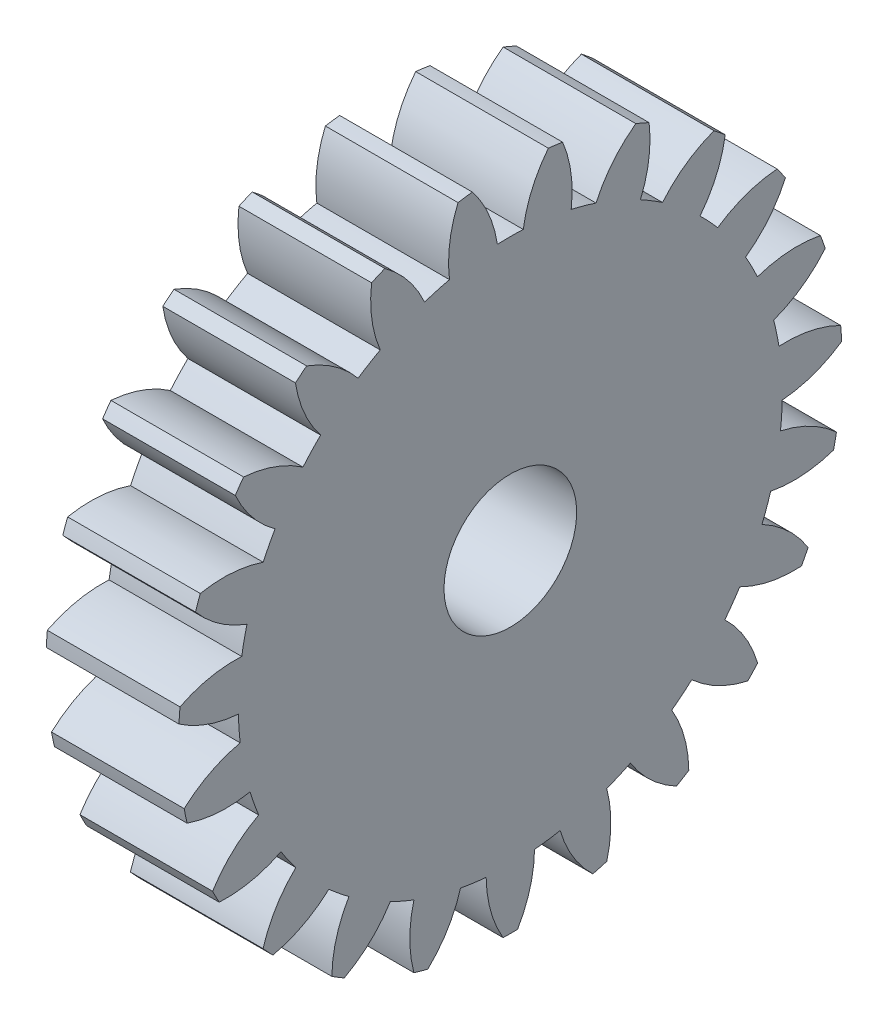
SolidWorks part; units mm, degrees
ref_plane "Plane1" through (0, 0, 0) normal (0, 0, 1) x (1, 0, 0)
ref_plane "Plane2" through (0, 0, 0) normal (0, 1, 0) x (1, 0, 0)
ref_plane "Plane3" through (0, 0, 0) normal (1, 0, 0) x (0, 0, -1)
other "Configuration Table"
sketch "HoldingSke" plane through (0, 0, 0) normal (0, 1, 0) x (1, 0, 0)
  line L0 (0, 0) -> (0.9205, -0.3907)
  line L1 (-15, 0) -> (100, 0) construction
  line L2 (0, 0) -> (-2.1039, 2.3779)
  line L3 (0, 0) -> (-11.863, 4.5341)
  line L4 (0, 0) -> (7.9495, 3.3744)
  line L5 (0, 0) -> (-46.8476, -17.4728)
  line L6 (0, 0) -> (-4.1448, -2.7965)
  line L7 (-2.1039, 2.3779) -> (8.6586, 51.2059)
  line L8 (-76.2, 54.61) -> (-75.3, 54.61)
  line L9 (-71.009, 38.7566) -> (-53.1078, 45.2721)
  line L10 (-76.2, 71.12) -> (104.1128, 71.12)
  line L11 (0, 0) -> (-5, 0)
  line L12 (-76.2, 101.6) -> (-76.162, 101.6)
  line L13 (24.9733, 27.94) -> (52.9518, 28.4284)
  line L14 (24.9733, 27.94) -> (24.9743, 27.94)
  line L15 (24.9733, 27.94) -> (100.4006, 29.5858)
  line L16 (-63.627, -1) -> (-12.827, -1)
  circle A0 centre (0, 0) radius 2.5
  circle A1 centre (0, 0) radius 10.249
  circle A2 centre (0, 0) radius 37.5
  circle A3 centre (0, 0) radius 2.5
  dimension "MHD" = 20.498
  dimension "Hub_dia" = 75
  dimension "Bore" = 5
  dimension "MBD" = 5
  dimension "Num_teeth" = 23
  dimension "Pitch" = 1
  dimension "Overall_len" = 50
  dimension "Show_teeth" = 23
  dimension "Thickness" = 5
  dimension "OAL" = 50.0001
  dimension "T_dim" = 0.9
  dimension "Ap" = 20
  dimension "H" = 19.05
  dimension "Pitch_radius" = 180.3128
  dimension "Width" = 5
  dimension "Backlash" = 0.038
  dimension "Addendum_fac" = 1
  dimension "Dedendum_fac" = 1.25
  dimension "Clearance_fac" = 0.25
  dimension "Dedendum_add" = 0.001
  dimension "Module" = 1
sketch "BasProSke" plane through (0, 0, 0) normal (0, 1, 0) x (1, 0, 0)
  line L0 (-10, 0) -> (60, 0) construction
  line L1 (0, 0) -> (0, 12.5)
  line L2 (0, 0) -> (5, 0)
  line L3 (5, 0) -> (5, 12.5)
  line L4 (5, 12.5) -> (0, 12.5)
  dimension "Thickness" = 5
  dimension "Diameter" = 25
revolve "Base-Revolve" add sketch "BasProSke" angle 360 about L0
sketch "TooCutSke" plane through (0, 0, 0) normal (1, 0, 0) x (0, 0, -1)
  line L1 (0, 0) -> (0, 107) construction
  line L2 (0, 0) -> (-0.8513, 11.4685) construction
  line L3 (0, 0) -> (-3.1257, 22.7413) construction
  line L4 (-0.8513, 11.4685) -> (-1.5629, 11.3706) construction
  arc A0 (0.4871, 10.2374) -> (-0.4871, 10.2374) centre (0, 0) ccw
  arc A1 (1.4505, 12.4411) -> (-1.4505, 12.4411) centre (0, 0) ccw
  circle A2 centre (0, 0) radius 11.5 construction
  circle A3 centre (0, 0) radius 10.8065 construction
  arc A4 (-0.4871, 10.2374) -> (-1.4505, 12.4411) centre (-5.037, 9.5608) ccw
  arc A5 (1.4505, 12.4411) -> (0.4871, 10.2374) centre (5.037, 9.5608) ccw
  dimension "Root_dia" = 20.498
  dimension "Overcut_dia" = 25.0508
  dimension "Pitch_dia" = 23
  dimension "Base_dia" = 21.6129
  dimension "Flank_rad" = 4.6
  dimension "Half_ang" = 7.826
  dimension "Half_CT" = 0.7183
extrude "ToothCut" cut sketch "TooCutSke" along normal through all
fillet "Breaks" [suppressed] radius 0.02
fillet "RootFillets" [suppressed] radius 0.251
pattern_circular "TeethCuts" count 23 every 15.652 about axis through (-10, 0, 0) along (1, 0, 0) of "ToothCut", "RootFillets", "Breaks"
sketch "HubNeaOneSke" plane through (0, 0, 0) normal (-1, 0, 0) x (0, 0, 1)
  circle A0 centre (0, 0) radius 10.249
  dimension "Diameter" = 20.498
extrude "HubNearOne" [suppressed] add sketch "HubNeaOneSke" along normal blind 45.0001
sketch "HubNeaBotSke" plane through (0, 0, 0) normal (-1, 0, 0) x (0, 0, 1)
  circle A0 centre (0, 0) radius 10.249
  dimension "Diameter" = 20.498
extrude "HubNearBoth" [suppressed] add sketch "HubNeaBotSke" along normal blind 22.5
ref_plane "FarPln" through (5, 0, 0) normal (1, 0, 0) x (0, 0, -1)
sketch "HubFarSke" plane through (5, 0, 0) normal (1, 0, 0) x (0, 0, -1)
  circle A0 centre (0, 0) radius 10.249
  dimension "Diameter" = 20.498
extrude "HubFar" [suppressed] add sketch "HubFarSke" along normal blind 22.5
sketch "BorSke" plane through (0, 0, 0) normal (1, 0, 0) x (0, 0, -1)
  circle A0 centre (0, 0) radius 2.5
  dimension "Diameter" = 5
extrude "Bore" cut sketch "BorSke" along normal mid plane 100.0001
sketch "KeySke" plane through (0, 0, 0) normal (1, 0, 0) x (0, 0, -1)
  line L0 (-1, 0) -> (-1, 3.4)
  line L1 (-1, 3.4) -> (1, 3.4)
  line L2 (1, 3.4) -> (1, 0)
  line L3 (0, 0) -> (0, 34) construction
  line L4 (-1, 0) -> (1, 0)
  dimension "Offset" = 3.4
  dimension "Width" = 2
extrude "Keyway" [suppressed] cut sketch "KeySke" along normal mid plane 100.0001
pattern_circular "Keyway2" [suppressed] count 2 every 90 about axis through (-10, 0, 0) along (1, 0, 0)
equation "' \"Module@HoldingSke\" = 6.35"
equation "' \"Num_teeth@HoldingSke\" = 12"
equation "' \"Ap@HoldingSke\" =  20"
equation "' \"Ap@HoldingSke\" = 20"
equation "' \"Width@HoldingSke\" = 0.5 * 25.4"
equation "' \"Hub_dia@HoldingSke\"= 1 * 25.4"
equation "' \"Hub_dia@HoldingSke\" = 1 * 25.4"
equation "' \"Overall_len@HoldingSke\" = 1.0 * 25.4"
equation "' \"Bore@HoldingSke\" = 0.75 * 25.4"
equation "' \"T_dim@HoldingSke\" = 0.1 * 25.4"
equation "' \"Width@KeySke\" = 0.25 * 25.4"
equation "' \"Show_teeth@HoldingSke\" = 13"
equation "' \"Backlash@HoldingSke\" = 0.009 * 25.4"
equation "' \"Addendum_fac@HoldingSke\" = 1.0"
equation "' \"Dedendum_fac@HoldingSke\" = 1.25"
equation "' \"Dedendum_add@HoldingSke\" = 0.00005 * 25.4"
equation "' \"Clearance_fac@HoldingSke\" = 0.25"
equation "\"Pitch@HoldingSke\" = 1 / \"Module@HoldingSke\""
equation "\"Overcut_dia@TooCutSke\" = (\"Num_teeth@HoldingSke\" + 2 * \"Addendum_fac@HoldingSke\") / \"Pitch@HoldingSke\" + 0.002 * 25.4"
equation "\"Pitch_dia@TooCutSke\" = \"Num_teeth@HoldingSke\" / \"Pitch@HoldingSke\""
equation "\"Base_dia@TooCutSke\" = \"Num_teeth@HoldingSke\" / \"Pitch@HoldingSke\" * cos((\"Ap@HoldingSke\"  * 3.14159265 / 180))"
equation "\"Root_dia@TooCutSke\" = (\"Num_teeth@HoldingSke\" + 2) / \"Pitch@HoldingSke\" - 2 * (\"Addendum_fac@HoldingSke\" + \"Dedendum_fac@HoldingSke\") / \"Pitch@HoldingSke\" - \"Dedendum_add@HoldingSke\" * 2"
equation "\"Half_ang@TooCutSke\" = 180 / \"Num_teeth@HoldingSke\""
equation "\"Half_CT@TooCutSke\" = \"Num_teeth@HoldingSke\" / \"Pitch@HoldingSke\" * sin((3.14159265 / 2 / \"Num_teeth@HoldingSke\")) / 2 - 7 * \"Backlash@HoldingSke\" / 4"
equation "\"Flank_rad@TooCutSke\" = \"Num_teeth@HoldingSke\" / \"Pitch@HoldingSke\" / 5"
equation "\"Radius@RootFillets\" = \"Clearance_fac@HoldingSke\" / \"Pitch@HoldingSke\" + \"Dedendum_add@HoldingSke\""
equation "\"Break_rad@Breaks\" = 0.02 / \"Pitch@HoldingSke\""
equation "\"Thickness@HoldingSke\" = \"Width@HoldingSke\""
equation "\"OAL@HoldingSke\" = \"Thickness@HoldingSke\""
equation "\"MHD@HoldingSke\" = (\"Num_teeth@HoldingSke\" + 2) / \"Pitch@HoldingSke\" - 2 * (\"Addendum_fac@HoldingSke\" + \"Dedendum_fac@HoldingSke\")  / \"Pitch@HoldingSke\" - \"Dedendum_add@HoldingSke\" * 2"
equation "\"MBD@HoldingSke\" = (\"Num_teeth@HoldingSke\" + 2) / \"Pitch@HoldingSke\" - 2 * (\"Addendum_fac@HoldingSke\" + \"Dedendum_fac@HoldingSke\")  / \"Pitch@HoldingSke\" - \"Dedendum_add@HoldingSke\" * 2 - 0.002 * 25.4"
equation "\"MHD@HoldingSke\" = ((sgn( \"MHD@HoldingSke\" - \"Hub_dia@HoldingSke\" )-1)*( \"MHD@HoldingSke\" - \"Hub_dia@HoldingSke\" ))/-2+ \"Hub_dia@HoldingSke\""
equation "\"MBD@HoldingSke\" = ((sgn( \"MBD@HoldingSke\" - \"Bore@HoldingSke\" )-1)*( \"MBD@HoldingSke\" - \"Bore@HoldingSke\" ))/-2+ \"Bore@HoldingSke\""
equation "\"OAL@HoldingSke\" = ((sgn( \"OAL@HoldingSke\" - \"Overall_len@HoldingSke\" )+1)*( \"OAL@HoldingSke\" - \"Overall_len@HoldingSke\" ))/2 + \"Overall_len@HoldingSke\" + 0.000002 * 25.4"
equation "\"Num_teeth@TeethCuts\" = int( \"Show_teeth@HoldingSke\" ) + 1"
equation "\"Num_teeth@TeethCuts\" = ((sgn( \"Num_teeth@TeethCuts\" - \"Num_teeth@HoldingSke\" )-1)*( \"Num_teeth@TeethCuts\" - \"Num_teeth@HoldingSke\" ))/-2+ \"Num_teeth@HoldingSke\""
equation "\"Num_teeth@TeethCuts\" = ((sgn( \"Num_teeth@TeethCuts\" - 2.0)+1)*( \"Num_teeth@TeethCuts\" - 2.0))/2 +2.0"
equation "\"Angle@TeethCuts\" = 360.0 / \"Num_teeth@HoldingSke\""
equation "\"Diameter@BasProSke\" = (\"Num_teeth@HoldingSke\" + 2 * \"Addendum_fac@HoldingSke\") / \"Pitch@HoldingSke\""
equation "\"Thickness@BasProSke\"  = \"Thickness@HoldingSke\""
equation "' \"Fillet_rad@BasProSke\" =  \"Thickness@HoldingSke\" * 0.05"
equation "' \"Fillet_rad@BasProSke\" = \"Thickness@HoldingSke\" * 0.05"
equation "\"MHD@HoldingSke\" = ((sgn( \"MHD@HoldingSke\" - \"Root_dia@TooCutSke\" )-1)*( \"MHD@HoldingSke\" - \"Root_dia@TooCutSke\" ))/-2+ \"Root_dia@TooCutSke\""
equation "\"Diameter@HubNeaOneSke\" = \"MHD@HoldingSke\""
equation "\"Length@HubNearOne\" = \"OAL@HoldingSke\" - \"Thickness@BasProSke\""
equation "\"Diameter@HubNeaBotSke\" = \"MHD@HoldingSke\""
equation "\"Length@HubNearBoth\" = ( \"OAL@HoldingSke\" - \"Thickness@BasProSke\" ) / 2.0"
equation "\"Thickness@FarPln\" = \"Thickness@BasProSke\""
equation "\"Diameter@HubFarSke\" = \"MHD@HoldingSke\""
equation "\"Length@HubFar\" = ( \"OAL@HoldingSke\" - \"Thickness@BasProSke\" ) / 2.0"
equation "\"Diameter@BorSke\" = \"MBD@HoldingSke\""
equation "\"D1@Bore\" = \"OAL@HoldingSke\" * 2.0"
equation "\"D1@Keyway\" = \"OAL@HoldingSke\" * 2.0"
equation "\"Offset@KeySke\" = \"T_dim@HoldingSke\" + \"MBD@HoldingSke\" / 2.0"
